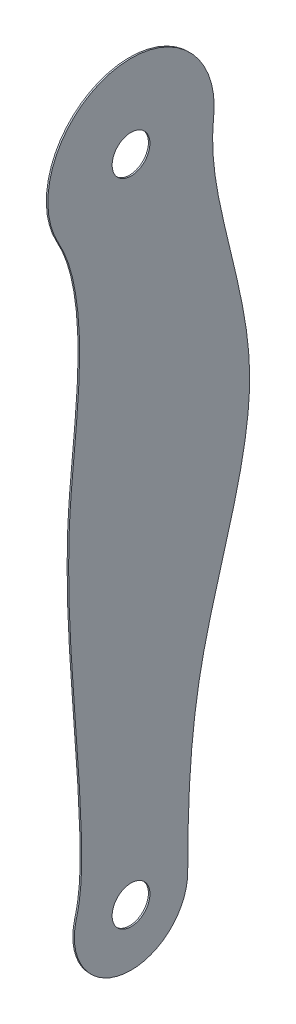
SolidWorks part; units mm, degrees
material "Teras S325"
ref_plane "Front Plane" through (0, 0, 0) normal (0, 0, 1) x (1, 0, 0)
ref_plane "Top Plane" through (0, 0, 0) normal (0, 1, 0) x (1, 0, 0)
ref_plane "Right Plane" through (0, 0, 0) normal (1, 0, 0) x (0, 0, -1)
sketch "Sketch3" plane through (0, 0, 0) normal (1, 0, 0) x (0, 0, -1)
  line L0 (0, 55) -> (0, -55) construction
  line L1 (0, 430) -> (0, 0) construction
  circle A0 centre (0, 430) radius 12.5
  circle A1 centre (0, 0) radius 12.5
  arc A2 (-36.207, 9.7622) -> (37.5, 0) centre (0, 0) ccw
  arc A3 (54.6523, 423.8253) -> (-48.0171, 403.1791) centre (0, 430) ccw
  spline S0 degree 3 poles (-48.0171, 403.1791) (-41.1124, 390.8179) (-27.9053, 336.9145) (-50.2084, 219.1735) (-32.2046, 102.5021) (-32.4237, 23.7943) (-36.207, 9.7622) knots 0 0 0 0 0.106359 0.411206 0.890018 1 1 1 1
  spline S1 degree 3 poles (54.6523, 423.8253) (52.5095, 404.8596) (61.6884, 350.9285) (93.7407, 248.1465) (40.8123, 127.8304) (37.5, 38.493) (37.5, 0) knots 0 0 0 0 0.133447 0.376559 0.731485 1 1 1 1
  dimension "D1" = 75
  dimension "D2" = 25
  dimension "D3" = 25
  dimension "D4" = 430
  dimension "D5" = 110
extrude "Extrude1" add sketch "Sketch3" along normal mid plane 1
